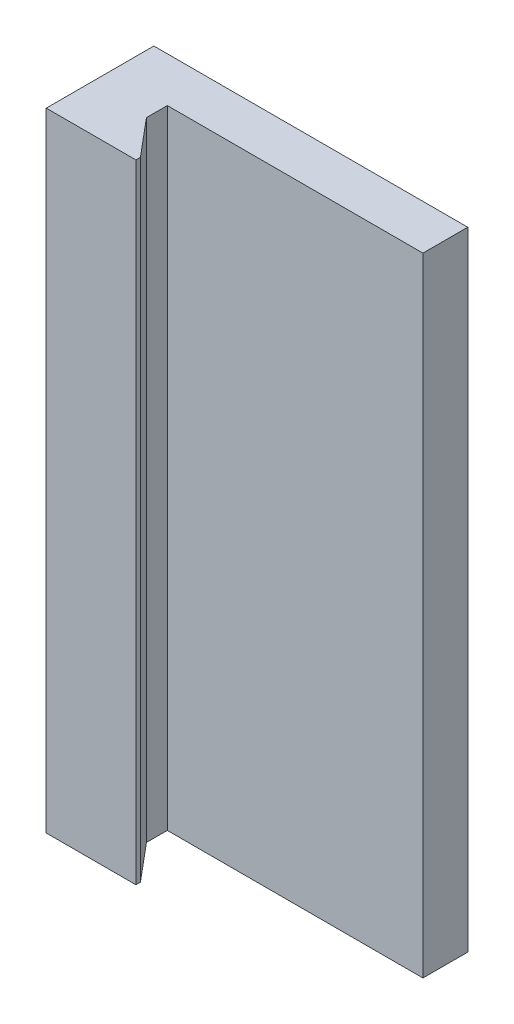
SolidWorks part; units mm, degrees
ref_plane "前视基准面" through (0, 0, 0) normal (0, 0, 1) x (1, 0, 0)
ref_plane "上视基准面" through (0, 0, 0) normal (0, 1, 0) x (1, 0, 0)
ref_plane "右视基准面" through (0, 0, 0) normal (1, 0, 0) x (0, 0, -1)
other "Configuration Table"
sketch "草图1" plane through (0, 0, 0) normal (0, 0, 1) x (1, 0, 0)
  line L1 (0, 0) -> (35, 0)
  line L2 (0, 0) -> (0, -70)
  line L3 (0, -70) -> (35, -70)
  line L4 (35, 0) -> (35, -70)
  dimension "D1" = 70
  dimension "D2" = 35
extrude "凸台-拉伸1" add sketch "草图1" along normal blind 12
sketch "草图2" plane through (0, -70, 0) normal (0, -1, 0) x (1, 0, 0)
  line L0 (10, 12) -> (10, 11.5)
  line L1 (0, 12) -> (35, 12) construction
  line L3 (6.5, 5) -> (35, 5)
  line L4 (35, 12) -> (35, 0) construction
  line L5 (10, 12) -> (35, 12)
  line L6 (35, 12) -> (35, 5)
  line L7 (10, 11.5) -> (6.5, 7.3289)
  line L8 (6.5, 7.3289) -> (6.5, 5)
  line L9 (0, 12) -> (0, 0) construction
  point P13 (7.8282, 8.4991)
  dimension "D1" = 0.5
  dimension "D2" = 140
  dimension "D3" = 7
  dimension "D4" = 3.5
  dimension "D5" = 10
extrude "切除-拉伸1" cut sketch "草图2" against normal up to next
